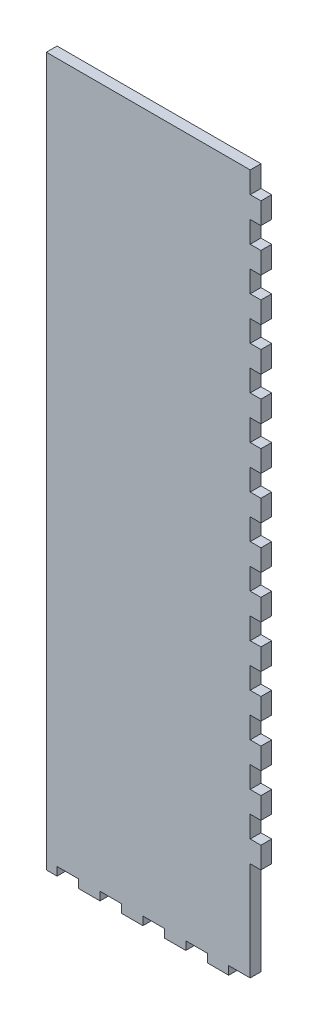
SolidWorks part; units mm, degrees
ref_plane "Plan de face" through (0, 0, 0) normal (0, 0, 1) x (1, 0, 0)
ref_plane "Plan de dessus" through (0, 0, 0) normal (0, 1, 0) x (1, 0, 0)
ref_plane "Plan de droite" through (0, 0, 0) normal (1, 0, 0) x (0, 0, -1)
sketch "Esquisse1" plane through (0, 0, 0) normal (0, 0, 1) x (1, 0, 0)
  line L1 (0, 0) -> (100, 0)
  line L2 (0, 0) -> (0, 330)
  line L3 (0, 330) -> (100, 330)
  line L4 (100, 0) -> (100, 330)
  dimension "D1" = 100
  dimension "D2" = 330
extrude "Boss.-Extru.1" add sketch "Esquisse1" along normal blind 5 contours L2 L1 L4 L3
sketch "Esquisse3" plane through (0, 0, 0) normal (0, 0, 1) x (1, 0, 0)
  line L0 (100, 0) -> (100, 330) construction
  line L1 (100, 330) -> (95, 330)
  line L2 (100, 330) -> (100, 320)
  line L3 (100, 320) -> (95, 320)
  line L4 (95, 330) -> (95, 320)
  line L5 (0, 330) -> (100, 330) construction
  line L6 (100, 310) -> (100, 300)
  line L7 (100, 310) -> (95, 310)
  line L8 (95, 310) -> (95, 300)
  line L9 (100, 300) -> (95, 300)
  line L10 (100, 290) -> (100, 280)
  line L11 (100, 290) -> (95, 290)
  line L12 (95, 290) -> (95, 280)
  line L13 (100, 280) -> (95, 280)
  line L14 (100, 270) -> (100, 260)
  line L15 (100, 270) -> (95, 270)
  line L16 (95, 270) -> (95, 260)
  line L17 (100, 260) -> (95, 260)
  line L18 (100, 250) -> (100, 240)
  line L19 (100, 250) -> (95, 250)
  line L20 (95, 250) -> (95, 240)
  line L21 (100, 240) -> (95, 240)
  line L22 (100, 230) -> (100, 220)
  line L23 (100, 230) -> (95, 230)
  line L24 (95, 230) -> (95, 220)
  line L25 (100, 220) -> (95, 220)
  line L26 (100, 210) -> (100, 200)
  line L27 (100, 210) -> (95, 210)
  line L28 (95, 210) -> (95, 200)
  line L29 (100, 200) -> (95, 200)
  line L30 (100, 190) -> (100, 180)
  line L31 (100, 190) -> (95, 190)
  line L32 (95, 190) -> (95, 180)
  line L33 (100, 180) -> (95, 180)
  line L34 (100, 170) -> (100, 160)
  line L35 (100, 170) -> (95, 170)
  line L36 (95, 170) -> (95, 160)
  line L37 (100, 160) -> (95, 160)
  line L38 (100, 150) -> (100, 140)
  line L39 (100, 150) -> (95, 150)
  line L40 (95, 150) -> (95, 140)
  line L41 (100, 140) -> (95, 140)
  line L42 (100, 130) -> (100, 120)
  line L43 (100, 130) -> (95, 130)
  line L44 (95, 130) -> (95, 120)
  line L45 (100, 120) -> (95, 120)
  line L46 (100, 110) -> (100, 100)
  line L47 (100, 110) -> (95, 110)
  line L48 (95, 110) -> (95, 100)
  line L49 (100, 100) -> (95, 100)
  line L50 (100, 90) -> (100, 80)
  line L51 (100, 90) -> (95, 90)
  line L52 (95, 90) -> (95, 80)
  line L53 (100, 80) -> (95, 80)
  line L54 (100, 70) -> (100, 60)
  line L55 (100, 70) -> (95, 70)
  line L56 (95, 70) -> (95, 60)
  line L57 (100, 60) -> (95, 60)
  line L58 (100, 50) -> (100, 40)
  line L60 (95, 50) -> (95, 40)
  line L61 (100, 50) -> (95, 50)
  line L62 (100, 0) -> (85, 0)
  line L63 (100, 40) -> (95, 40) [skipped]
  line L65 (0, 0) -> (100, 0) construction
  line L67 (100, 0) -> (100, 40)
  line L72 (85, 0) -> (85, 3.8984)
  line L73 (75, 0) -> (75, 3.8984)
  line L74 (75, 0) -> (65, 0)
  line L75 (65, 0) -> (65, 3.8984)
  line L76 (75, 3.8984) -> (65, 3.8984)
  line L77 (55, 0) -> (55, 3.8984)
  line L78 (55, 0) -> (45, 0)
  line L79 (45, 0) -> (45, 3.8984)
  line L80 (55, 3.8984) -> (45, 3.8984)
  line L81 (35, 0) -> (35, 3.8984)
  line L82 (35, 0) -> (25, 0)
  line L83 (25, 0) -> (25, 3.8984)
  line L84 (35, 3.8984) -> (25, 3.8984)
  line L85 (15, 0) -> (15, 3.8984)
  line L86 (15, 0) -> (5, 0)
  line L87 (5, 0) -> (5, 3.8984)
  line L88 (15, 3.8984) -> (5, 3.8984)
  line L90 (85, 3.8984) -> (95, 3.8984)
  line L91 (95, 40) -> (95, 3.8984)
  dimension "D1" = 5
  dimension "D2" = 10
  dimension "D6" = 10
  dimension "D3" = 14
  dimension "D4" = 2
  dimension "D7" = 5
extrude "Enlèv. mat.-Extru.1" cut sketch "Esquisse3" along normal through all
